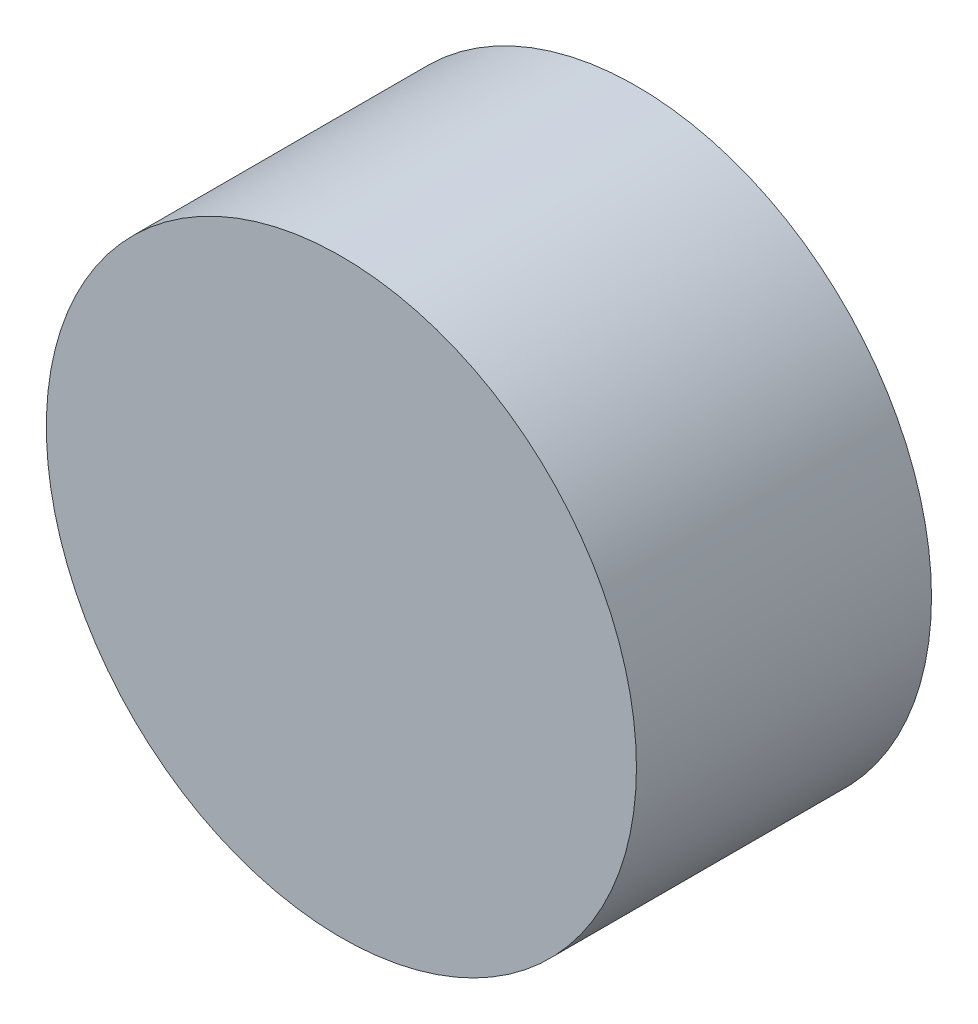
SolidWorks part; units mm, degrees
material "普通碳钢"
ref_plane "前视基准面" through (0, 0, 0) normal (0, 0, 1) x (1, 0, 0)
ref_plane "上视基准面" through (0, 0, 0) normal (0, 1, 0) x (1, 0, 0)
ref_plane "右视基准面" through (0, 0, 0) normal (1, 0, 0) x (0, 0, -1)
sketch "草图1" plane through (0, 0, 0) normal (0, 0, 1) x (1, 0, 0)
  circle A0 centre (0, 0) radius 30
  dimension "D1" = 60
extrude "凸台-拉伸1" add sketch "草图1" along normal blind 30
